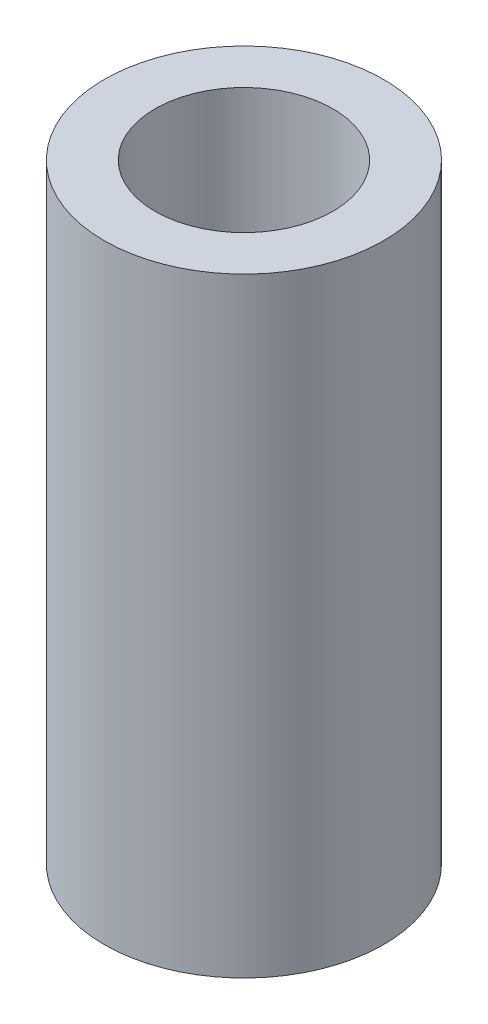
SolidWorks part; units mm, degrees
ref_plane "Front Plane" through (0, 0, 0) normal (0, 0, 1) x (1, 0, 0)
ref_plane "Top Plane" through (0, 0, 0) normal (0, 1, 0) x (1, 0, 0)
ref_plane "Right Plane" through (0, 0, 0) normal (1, 0, 0) x (0, 0, -1)
sketch "Sketch1" plane through (0, 0, 0) normal (0, 1, 0) x (1, 0, 0)
  circle A0 centre (0, 0) radius 1.75
  circle A1 centre (0, 0) radius 2.75
  dimension "D1" = 3.5
  dimension "D2" = 5.5
extrude "Boss-Extrude1" add sketch "Sketch1" along normal blind 12
